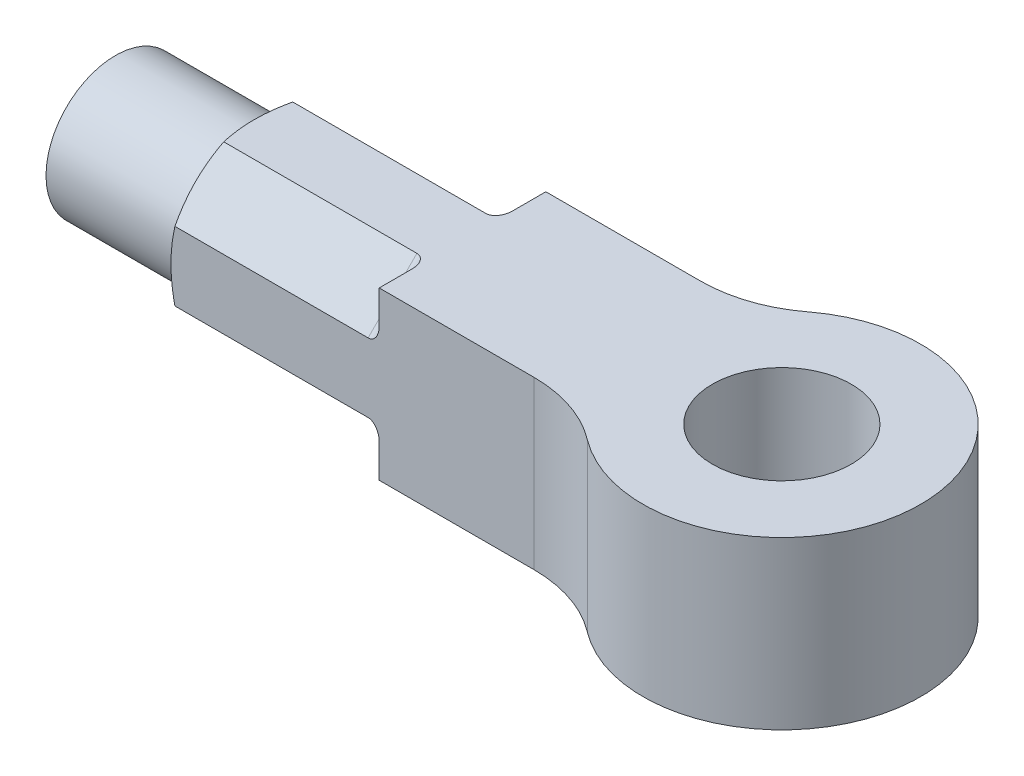
SolidWorks part; units mm, degrees
ref_plane "Front Plane" through (0, 0, 0) normal (0, 0, 1) x (1, 0, 0)
ref_plane "Top Plane" through (0, 0, 0) normal (0, 1, 0) x (1, 0, 0)
ref_plane "Right Plane" through (0, 0, 0) normal (1, 0, 0) x (0, 0, -1)
sketch "Sketch1" plane through (0, 0, 0) normal (0, 1, 0) x (1, 0, 0)
  line L0 (0, 0) -> (50000, 0) construction
  line L1 (-29.6648, 15) -> (-95, 15)
  line L2 (-95, 15) -> (-95, -15)
  line L3 (-29.6648, -15) -> (-95, -15)
  circle A0 centre (0, 0) radius 12.5
  arc A1 (-15.1351, -19.898) -> (-15.1351, 19.898) centre (0, 0) ccw
  arc A2 (-29.6648, -15) -> (-15.1351, -19.898) centre (-29.6648, -39) cw
  arc A3 (-29.6648, 15) -> (-15.1351, 19.898) centre (-29.6648, 39) ccw
  point P9 (-95, 0)
  point P12 (-20, -15)
  point P15 (-20, 15)
  dimension "D1" = 25
  dimension "D2" = 50
  dimension "D5" = 24
  dimension "D3" = 30
  dimension "D4" = 95
extrude "Boss-Extrude1" add sketch "Sketch1" along normal mid plane 30
sketch "Sketch2" plane through (-95, 0, 0) normal (-1, 0, 0) x (0, 0, 1)
  line L0 (-15, 15) -> (15, 15) construction
  line L1 (6.2132, 15) -> (-6.2132, 15)
  line L2 (-6.2132, 15) -> (-15, 6.2132)
  line L3 (-15, 6.2132) -> (-15, -6.2132)
  line L4 (-15, -6.2132) -> (-6.2132, -15)
  line L5 (-6.2132, -15) -> (6.2132, -15)
  line L6 (6.2132, -15) -> (15, -6.2132)
  line L7 (15, -6.2132) -> (15, 6.2132)
  line L8 (15, 6.2132) -> (6.2132, 15)
  circle A0 centre (0, 0) radius 15 construction
extrude "Cut-Extrude1" cut sketch "Sketch2" against normal blind 37.5 flip side to cut
sketch "Sketch3" plane through (-95, 0, 0) normal (-1, 0, 0) x (0, 0, 1)
  circle A0 centre (0, 0) radius 12.5
  dimension "D1" = 25
extrude "Boss-Extrude2" add sketch "Sketch3" along normal blind 25
fillet "Fillet1" radius 2 4 edges at (-57.5, 10.6066, -10.6066) (-57.5, -10.6066, -10.6066) (-57.5, -10.6066, 10.6066) (-57.5, 10.6066, 10.6066)
sketch "Sketch4" plane through (0, 0, 0) normal (0, 0, 1) x (1, 0, 0)
  line L0 (-95, 15) -> (-95, 27.0023)
  line L1 (-95, 27.0023) -> (-88.0705, 27.0023)
  line L2 (-88.0705, 27.0023) -> (-95, 15)
  line L3 (0, 0) -> (-120, 0) construction
  line L4 (-120, 12.5) -> (-120, -12.5) construction
  dimension "D1" = 30
revolve "Cut-Revolve1" cut sketch "Sketch4" angle 360 about L3
